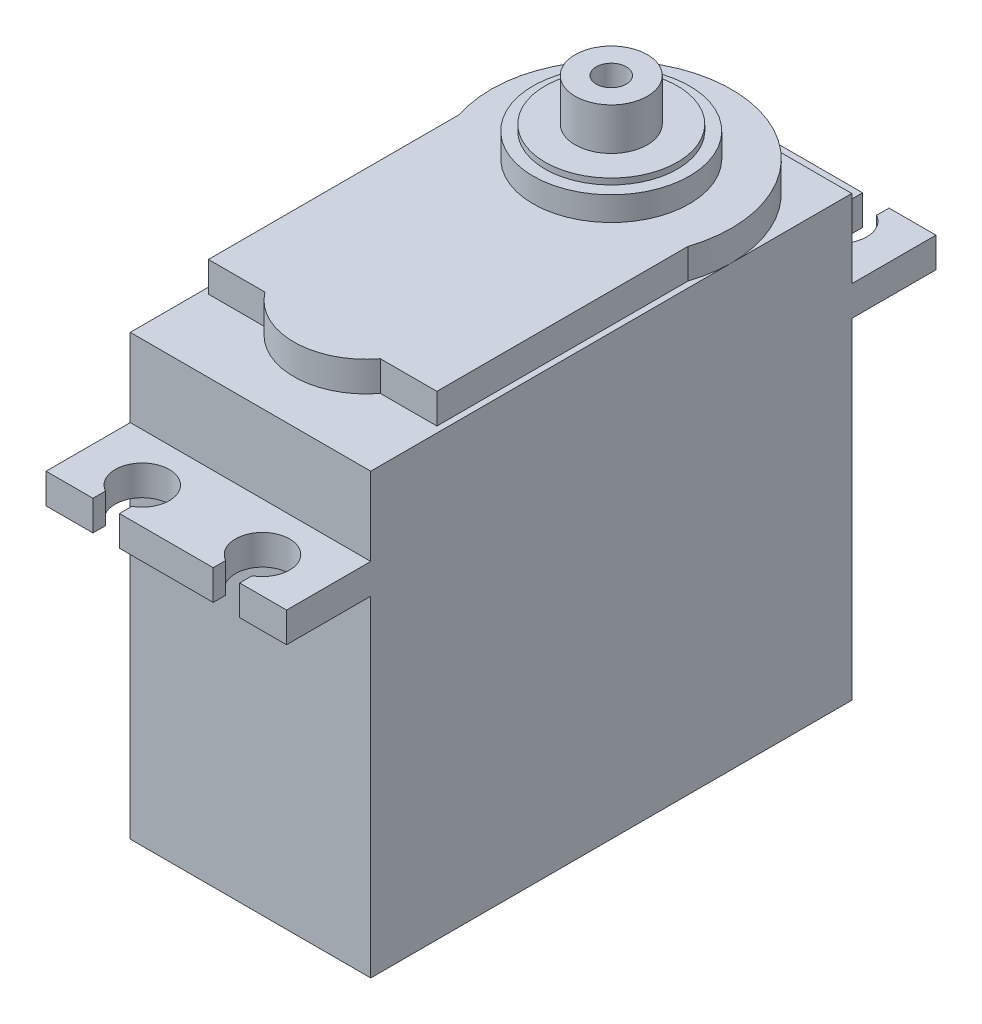
SolidWorks part; units mm, degrees
ref_plane "前视基准面" through (0, 0, 0) normal (0, 0, 1) x (1, 0, 0)
ref_plane "上视基准面" through (0, 0, 0) normal (0, 1, 0) x (1, 0, 0)
ref_plane "右视基准面" through (0, 0, 0) normal (1, 0, 0) x (0, 0, -1)
sketch "草图1" plane through (0, 0, 0) normal (0, 1, 0) x (1, 0, 0)
  line L1 (-10, -20) -> (10, -20)
  line L2 (-10, -20) -> (-10, 20)
  line L3 (-10, 20) -> (10, 20)
  line L4 (10, -20) -> (10, 20)
  line L5 (-10, -20) -> (10, 20) construction
  line L6 (-10, 20) -> (10, -20) construction
  point P0 (0, 0)
  dimension "D1" = 40
  dimension "D2" = 20
extrude "凸台-拉伸1" add sketch "草图1" along normal blind 36.5
sketch "草图2" plane through (0, 36.5, 0) normal (0, 1, 0) x (1, 0, 0)
  line L0 (0, 20) -> (0, -20) construction
  line L1 (10, 20) -> (-10, 20) construction
  line L2 (-10, -20) -> (10, -20) construction
  line L3 (-9.5, 6.8775) -> (-9.5, -14)
  line L4 (4.797, -14) -> (9.5, -14)
  line L5 (9.5, -14) -> (9.5, 6.8775)
  line L6 (-9.5, -14) -> (-4.797, -14)
  line L7 (-10, 20) -> (-10, -20) construction
  line L8 (10, -20) -> (10, 20) construction
  arc A0 (9.5, 6.8775) -> (-9.5, 6.8775) centre (0, 10) ccw
  arc A1 (-4.797, -14) -> (4.797, -14) centre (0, -10.396) ccw
  dimension "D1" = 20
  dimension "D2" = 0.5
  dimension "D5" = 12
  dimension "D3" = 0.5
  dimension "D4" = 6
extrude "凸台-拉伸2" add sketch "草图2" along normal blind 2.5
sketch "草图3" plane through (0, 39, 0) normal (0, 1, 0) x (1, 0, 0)
  line L0 (0, -20) -> (0, 20) construction
  line L1 (-10, -20) -> (10, -20) construction
  line L2 (0, 20) -> (-10, 20) construction
  arc A0 (9.5, 6.8775) -> (-9.5, 6.8775) centre (0, 10) ccw construction
  circle A1 centre (0, 10) radius 6.5
  dimension "D1" = 13
  dimension "D2" = 10
extrude "凸台-拉伸3" add sketch "草图3" along normal blind 2
sketch "草图4" plane through (0, 41, 0) normal (0, 1, 0) x (1, 0, 0)
  circle A0 centre (0, 10) radius 5.5
  dimension "D1" = 11
extrude "凸台-拉伸4" add sketch "草图4" along normal blind 0.5
sketch "草图5" plane through (0, 41.5, 0) normal (0, 1, 0) x (1, 0, 0)
  circle A0 centre (0, 10) radius 3
  circle A1 centre (0, 10) radius 1.25
  dimension "D1" = 6
  dimension "D2" = 2.5
extrude "凸台-拉伸5" add sketch "草图5" along normal blind 3.5 separate body
ref_plane "基准面1" through (0, 30, 0) normal (0, -1, 0) x (-1, 0, 0)
sketch "草图6" plane through (0, 30, 0) normal (0, -1, 0) x (-1, 0, 0)
  line L0 (0, 0) -> (-15.3294, 0) construction
  line L2 (10, 20) -> (10, 10) construction
  line L3 (10, 27) -> (6.1, 27)
  line L4 (10, 27) -> (10, 20)
  line L5 (5, -24) -> (5, -27.9952) construction
  line L6 (-10, 27) -> (-10, 20)
  line L7 (-10, 10) -> (-10, 20) construction
  line L8 (-6.1, -27) -> (-10, -27)
  line L9 (0, 20) -> (10, 20) construction
  line L10 (-10, 20) -> (0, 20) construction
  line L11 (0, 20) -> (10, 20)
  line L12 (-10, 20) -> (0, 20)
  line L13 (3.9, -27) -> (-3.9, -27)
  line L14 (-6.1, -25.9628) -> (-6.1, -27)
  line L15 (5, 24) -> (5, 27.9952) construction
  line L16 (6.1, 25.9628) -> (6.1, 27)
  line L17 (3.9, 25.9628) -> (3.9, 27)
  line L18 (-3.9, 25.9628) -> (-3.9, 27)
  line L19 (-6.1, 25.9628) -> (-6.1, 27)
  line L20 (3.9, 27) -> (-3.9, 27)
  line L21 (6.1, 24) -> (6.1, 27.9952) construction
  line L22 (-6.1, 27) -> (-10, 27)
  line L23 (3.9, 24) -> (3.9, 27.9952) construction
  line L24 (-3.9, -25.9628) -> (-3.9, -27)
  line L25 (3.9, -25.9628) -> (3.9, -27)
  line L26 (6.1, -25.9628) -> (6.1, -27)
  line L27 (-10, -20) -> (0, -20)
  line L28 (0, -20) -> (10, -20)
  line L29 (-10, -27) -> (-10, -20)
  line L30 (10, -27) -> (10, -20)
  line L31 (10, -27) -> (6.1, -27)
  arc A0 (3.9, 25.9628) -> (6.1, 25.9628) centre (5, 24) ccw
  arc A1 (-3.9, 25.9628) -> (-6.1, 25.9628) centre (-5, 24) cw
  arc A2 (-3.9, -25.9628) -> (-6.1, -25.9628) centre (-5, -24) ccw
  arc A3 (3.9, -25.9628) -> (6.1, -25.9628) centre (5, -24) cw
  dimension "D2" = 10
  dimension "D3" = 4.5
  dimension "D4" = 3
  dimension "D1" = 7
  dimension "D5" = 1.1
  dimension "D6" = 1.1
extrude "凸台-拉伸6" add sketch "草图6" along normal blind 2.5
